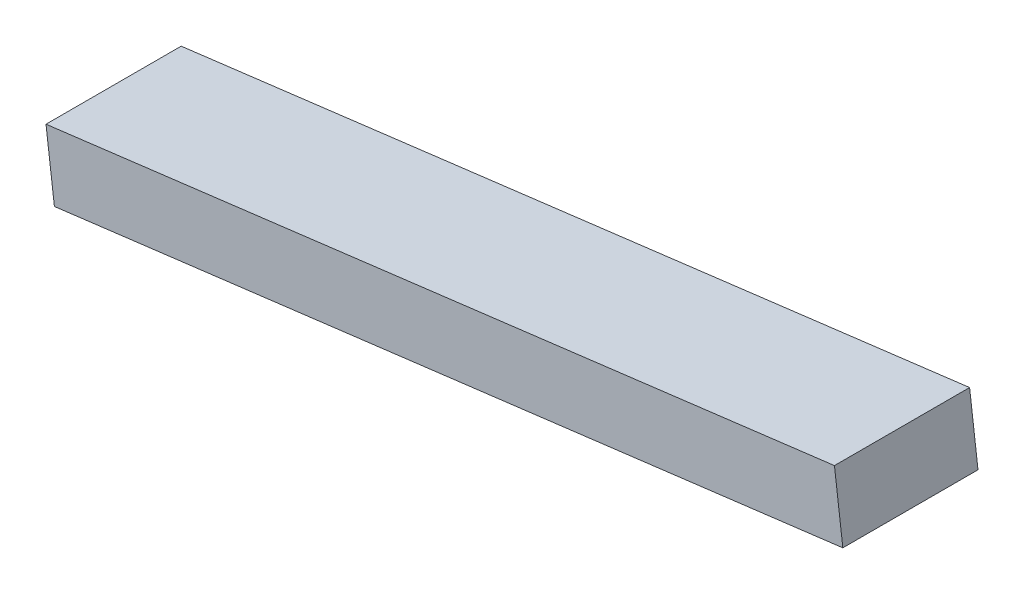
SolidWorks part; units mm, degrees
material "Balsa"
ref_plane "Front Plane" through (0, 0, 0) normal (0, 0, 1) x (1, 0, 0)
ref_plane "Top Plane" through (0, 0, 0) normal (0, 1, 0) x (1, 0, 0)
ref_plane "Right Plane" through (0, 0, 0) normal (1, 0, 0) x (0, 0, -1)
sketch "Sketch1" plane through (0, 0, -649.3965) normal (0, 0, 1) x (1, 0, 0)
  line L0 (368.571, 25.8277) -> (293.4805, 16.4388)
  line L2 (329.4729, 50.1459) -> (364.4047, 54.5135) construction
  line L3 (293.4805, 16.4388) -> (293.0866, 19.5893) construction
  line L4 (369.3588, 19.5268) -> (294.2684, 10.1379)
  line L5 (368.571, 25.8277) -> (369.3588, 19.5268)
  line L6 (293.4805, 16.4388) -> (294.2684, 10.1379)
  spline S2 degree 3 poles (266.7, -23.7693) (275.8805, -20.4431) (285.0295, -17.0322) (303.2447, -9.9898) (312.3076, -6.3596) (330.3153, 1.1877) (339.2629, 5.106) (356.9768, 13.3116) (365.7449, 17.5996) (374.396, 22.1319) knots 0 0 0 0 0.25 0.25 0.5 0.5 0.75 0.75 1 1 1 1 construction
  spline S3 degree 3 poles (374.396, 35.9161) (360.3505, 33.1321) (346.3121, 30.3121) (318.3815, 24.6902) (304.4894, 21.8871) (290.5967, 19.0875) knots 0 0 0 0 0.5 0.5 0.994877 0.994877 0.994877 0.994877 construction
  dimension "D1" = 6.35
  dimension "D2" = 3.175
  dimension "D3" = 2.54
extrude "Boss-Extrude1" add sketch "Sketch1" along normal blind 12.7 contours L4 L6 L0 L5
sketch "Sketch2" plane through (3.2816, -26.2454, 0) normal (0.1241, -0.9923, 0) x (0.9923, 0.1241, 0)
  line L0 (367.9117, -649.3965) -> (367.9117, -636.6965)
  line L4 (293.2525, -649.3965) -> (368.9277, -649.3965)
  line L5 (368.9277, -649.3965) -> (368.9277, -636.6965)
  line L6 (368.9277, -636.6965) -> (293.2525, -636.6965)
  line L7 (293.2525, -636.6965) -> (293.2525, -649.3965)
  line L8 (367.9117, -649.3965) -> (368.9277, -649.3965)
  line L9 (368.9277, -649.3965) -> (368.9277, -636.6965)
  line L10 (368.9277, -636.6965) -> (367.9117, -636.6965)
  dimension "D2" = 1.016
  dimension "D1" = 0
extrude "Cut-Extrude1" cut sketch "Sketch2" against normal through all
